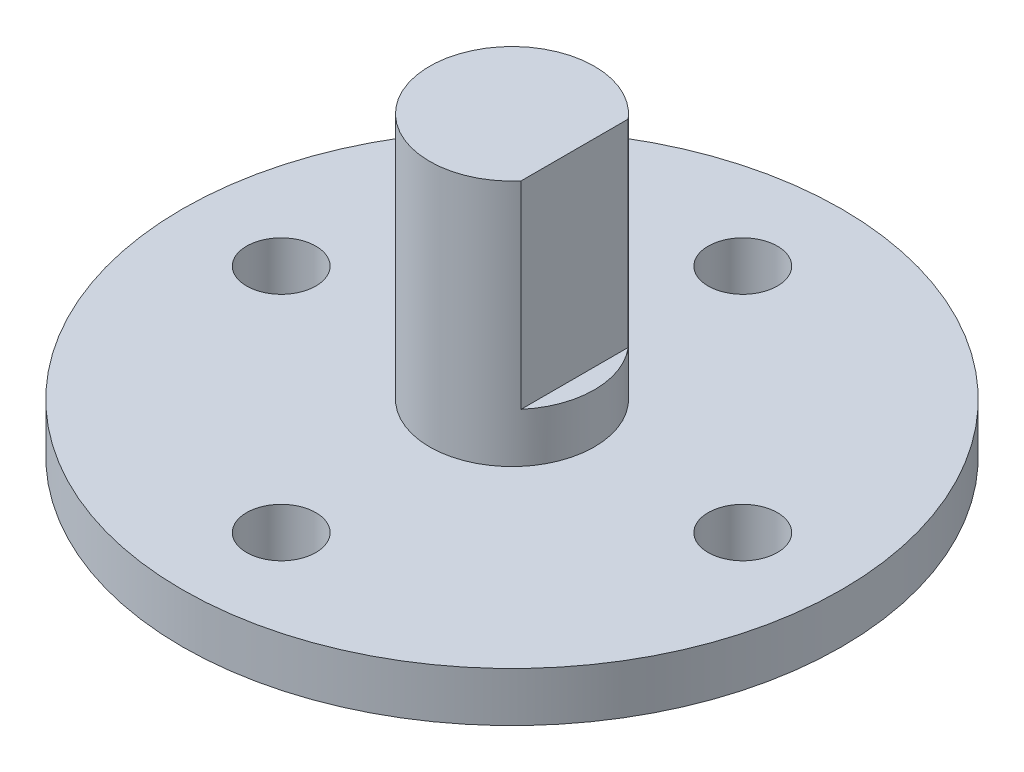
SolidWorks part; units mm, degrees
ref_plane "Front Plane" through (0, 0, 0) normal (0, 0, 1) x (1, 0, 0)
ref_plane "Top Plane" through (0, 0, 0) normal (0, 1, 0) x (1, 0, 0)
ref_plane "Right Plane" through (0, 0, 0) normal (1, 0, 0) x (0, 0, -1)
sketch "Sketch1" plane through (0, 0, 0) normal (0, 1, 0) x (1, 0, 0)
  circle A0 centre (0, 0) radius 20
  circle A1 centre (-14, 0) radius 2.1
  circle A2 centre (0, 14) radius 2.1
  circle A3 centre (14, 0) radius 2.1
  circle A4 centre (0, -14) radius 2.1
  point P14 (0, 0)
  dimension "D1" = 14
  dimension "D2" = 40
  dimension "D3" = 4
extrude "Boss-Extrude1" add sketch "Sketch1" along normal blind 3
sketch "Sketch2" plane through (0, 3, 0) normal (0, 1, 0) x (1, 0, 0)
  circle A0 centre (0, 0) radius 5
  dimension "D1" = 10
extrude "Boss-Extrude2" add sketch "Sketch2" along normal blind 15
sketch "Sketch3" plane through (0, 18, 0) normal (0, 1, 0) x (1, 0, 0)
  line L0 (3.8, 3.2496) -> (3.8, -3.2496)
  arc A0 (3.8, -3.2496) -> (3.8, 3.2496) centre (0, 0) ccw
  dimension "D1" = 10
  dimension "D2" = 3.8
extrude "Cut-Extrude1" cut sketch "Sketch3" against normal blind 12
